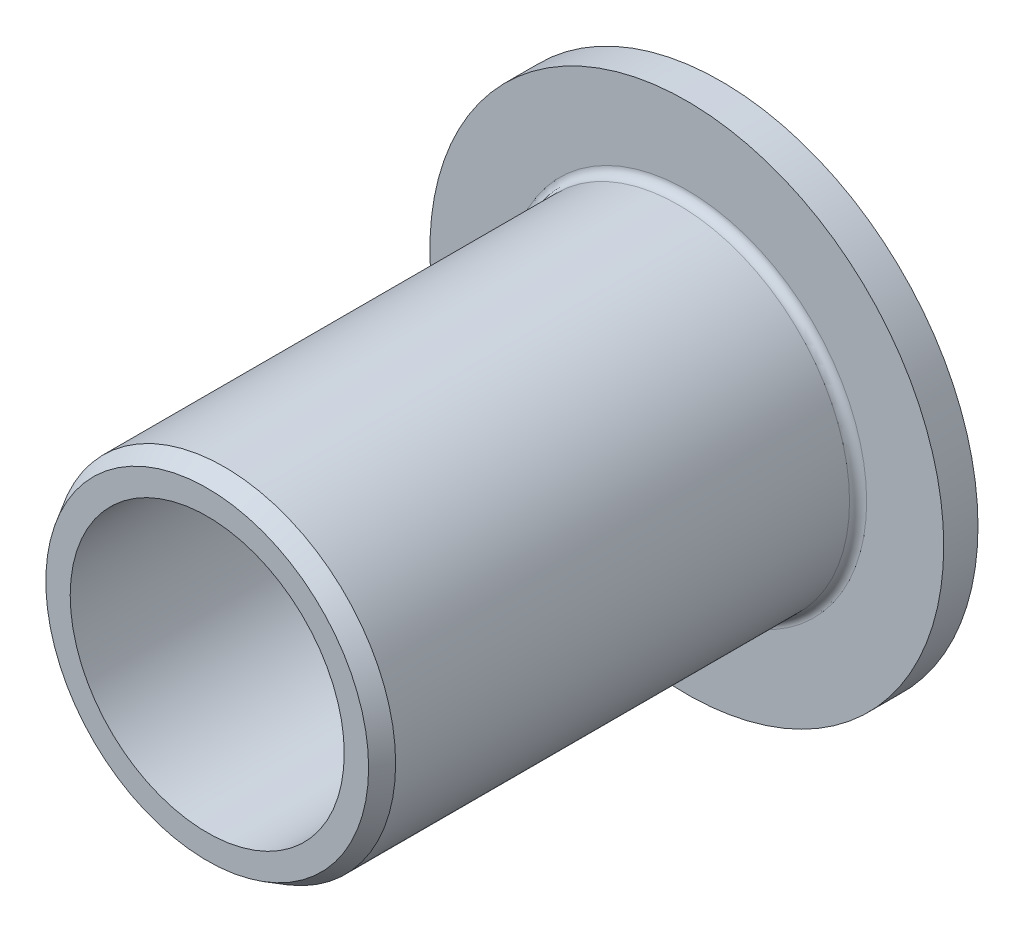
SolidWorks part; units mm, degrees
material "Igus T500"
ref_plane "Front Plane" through (0, 0, 0) normal (0, 0, 1) x (1, 0, 0)
ref_plane "Top Plane" through (0, 0, 0) normal (0, 1, 0) x (1, 0, 0)
ref_plane "Right Plane" through (0, 0, 0) normal (1, 0, 0) x (0, 0, -1)
ref_plane "Plane1" through (0, 0, 0) normal (0, 1, 0) x (-1, 0, 0)
sketch "Sketch1" plane through (0, 0, 0) normal (0, 1, 0) x (-1, 0, 0)
  line L0 (-5, 1) -> (-7.5, 1)
  line L1 (-7.5, 0) -> (-4, 0)
  line L2 (-4, 0) -> (-4, 15)
  line L3 (-4.7113, 15) -> (-5, 14.5)
  line L4 (-5, 14.5) -> (-5, 1)
  line L5 (0, 0) -> (0, 9.5) construction
  line L6 (-4, 15) -> (-4.7113, 15)
  line L8 (-7.5, 1) -> (-7.5, 0)
  dimension "D1" = 8
  dimension "D2" = 10
  dimension "D3" = 0.5
  dimension "D5" = 1
  dimension "FLANGE" = 15
  dimension "D7" = 30
  dimension "LENGTH" = 15
revolve "Revolve1" add sketch "Sketch1" angle 360 about L5
fillet "Fillet1" radius 0.25 1 edges at (5, 0, 1)
